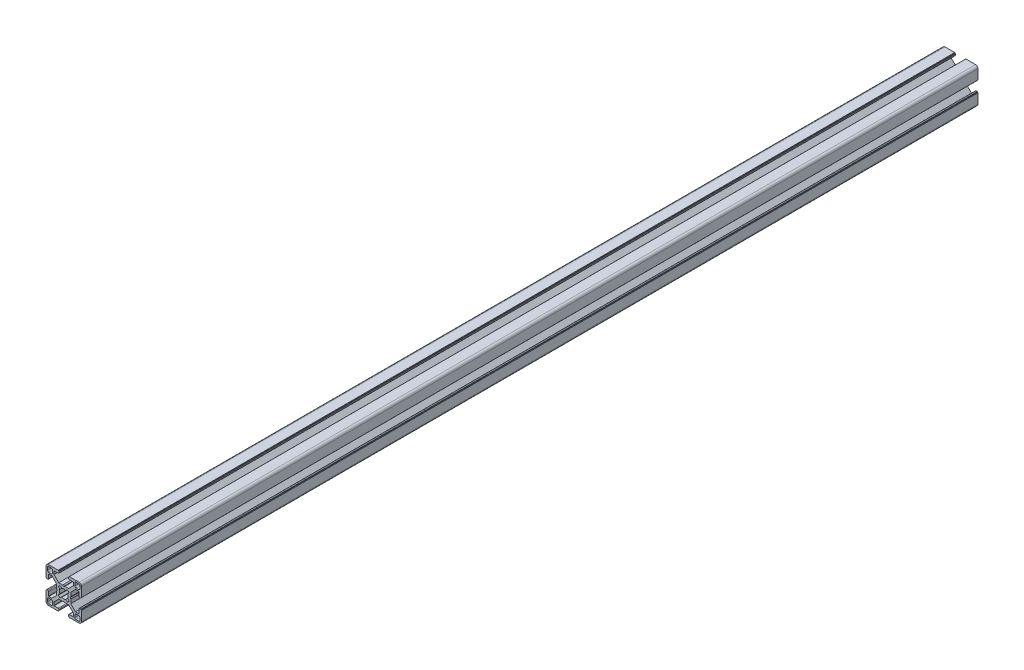
SolidWorks part; units mm, degrees
material "6063-T5"
ref_plane "前视基准面" through (0, 0, 0) normal (0, 0, 1) x (1, 0, 0)
ref_plane "上视基准面" through (0, 0, 0) normal (0, 1, 0) x (1, 0, 0)
ref_plane "右视基准面" through (0, 0, 0) normal (1, 0, 0) x (0, 0, -1)
ref_plane "基准面4" through (0, 0, 25) normal (0, 0, 1) x (1, 0, 0)
sketch "草图1" plane through (0, 0, 25) normal (0, 0, 1) x (1, 0, 0)
  line L0 (-12.7, 13.7) -> (-10.5, 13.7)
  line L1 (-9.5, 12.7) -> (-9.5, 10.5)
  line L2 (-10.5, 9.5) -> (-12.7, 9.5)
  line L3 (-13.7, 10.5) -> (-13.7, 12.7)
  line L4 (-10.5, -13.7) -> (-12.7, -13.7)
  line L5 (-13.7, -12.7) -> (-13.7, -10.5)
  line L6 (-12.7, -9.5) -> (-10.5, -9.5)
  line L7 (-9.5, -10.5) -> (-9.5, -12.7)
  line L8 (10.5, 13.7) -> (12.7, 13.7)
  line L9 (13.7, 12.7) -> (13.7, 10.5)
  line L10 (12.7, 9.5) -> (10.5, 9.5)
  line L11 (9.5, 10.5) -> (9.5, 12.7)
  line L12 (13.7, -10.5) -> (13.7, -12.7)
  line L13 (12.7, -13.7) -> (10.5, -13.7)
  line L14 (9.5, -12.7) -> (9.5, -10.5)
  line L15 (10.5, -9.5) -> (12.7, -9.5)
  line L16 (-3.1359, 4.5184) -> (-1.6001, 3.2806)
  line L17 (1.6001, 3.2806) -> (3.1359, 4.5184)
  line L18 (4.5053, 3.1547) -> (3.2806, 1.6001)
  line L19 (3.2806, -1.6001) -> (4.5053, -3.1547)
  line L20 (3.1359, -4.5184) -> (1.6001, -3.2806)
  line L21 (-1.6001, -3.2806) -> (-3.1359, -4.5184)
  line L22 (-4.5053, -3.1547) -> (-3.2806, -1.6001)
  line L23 (-3.2806, 1.6001) -> (-4.5053, 3.1547)
  line L24 (-4.05, 13.4) -> (-4.05, 14.3)
  line L25 (-4.25, 14.5) -> (-4.35, 14.5)
  line L26 (-4.55, 14.7) -> (-4.55, 14.8)
  line L27 (-4.75, 15) -> (-13, 15)
  line L28 (-15, 13) -> (-15, 4.75)
  line L29 (-14.8, 4.55) -> (-14.7, 4.55)
  line L30 (-14.5, 4.35) -> (-14.5, 4.25)
  line L31 (-14.3, 4.05) -> (-13.4, 4.05)
  line L32 (-12.8, 4.65) -> (-12.8, 8.05)
  line L33 (-12.6, 8.25) -> (-10.05, 8.25)
  line L34 (-10.05, 8.25) -> (-6.0045, 4.2045)
  line L35 (-6.0045, 4.2045) -> (-6.0045, 0.9)
  line L36 (-6.0045, 0.9) -> (-5.4849, 0)
  line L37 (-5.4849, 0) -> (-6.0045, -0.9)
  line L38 (-6.0045, -0.9) -> (-6.0045, -4.2045)
  line L39 (-6.0045, -4.2045) -> (-10.05, -8.25)
  line L40 (-10.05, -8.25) -> (-12.6, -8.25)
  line L41 (-12.8, -8.05) -> (-12.8, -4.65)
  line L42 (-13.4, -4.05) -> (-14.3, -4.05)
  line L43 (-14.5, -4.25) -> (-14.5, -4.35)
  line L44 (-14.7, -4.55) -> (-14.8, -4.55)
  line L45 (-15, -4.75) -> (-15, -13)
  line L46 (-13, -15) -> (-4.75, -15)
  line L47 (-4.55, -14.8) -> (-4.55, -14.7)
  line L48 (-4.35, -14.5) -> (-4.25, -14.5)
  line L49 (-4.05, -14.3) -> (-4.05, -13.4)
  line L50 (-4.65, -12.8) -> (-8.05, -12.8)
  line L51 (-8.25, -12.6) -> (-8.25, -10.05)
  line L52 (-8.25, -10.05) -> (-4.2045, -6)
  line L53 (-4.2045, -6) -> (-0.9, -6)
  line L54 (-0.9, -6) -> (0, -5.4849)
  line L55 (0, -5.4849) -> (0.9, -6)
  line L56 (0.9, -6) -> (4.2045, -6)
  line L57 (4.2045, -6) -> (8.25, -10.05)
  line L58 (8.25, -10.05) -> (8.25, -12.6)
  line L59 (8.05, -12.8) -> (4.65, -12.8)
  line L60 (4.05, -13.4) -> (4.05, -14.3)
  line L61 (4.25, -14.5) -> (4.35, -14.5)
  line L62 (4.55, -14.7) -> (4.55, -14.8)
  line L63 (4.75, -15) -> (13, -15)
  line L64 (15, -13) -> (15, -4.75)
  line L65 (14.8, -4.55) -> (14.7, -4.55)
  line L66 (14.5, -4.35) -> (14.5, -4.25)
  line L67 (14.3, -4.05) -> (13.4, -4.05)
  line L68 (12.8, -4.65) -> (12.8, -8.05)
  line L69 (12.6, -8.25) -> (10.05, -8.25)
  line L70 (10.05, -8.25) -> (6.0045, -4.2045)
  line L71 (6.0045, -4.2045) -> (6.0045, -0.9)
  line L72 (6.0045, -0.9) -> (5.4849, 0)
  line L73 (5.4849, 0) -> (6.0045, 0.9)
  line L74 (6.0045, 0.9) -> (6.0045, 4.2045)
  line L75 (6.0045, 4.2045) -> (10.05, 8.25)
  line L76 (10.05, 8.25) -> (12.6, 8.25)
  line L77 (12.8, 8.05) -> (12.8, 4.65)
  line L78 (13.4, 4.05) -> (14.3, 4.05)
  line L79 (14.5, 4.25) -> (14.5, 4.35)
  line L80 (14.7, 4.55) -> (14.8, 4.55)
  line L81 (15, 4.75) -> (15, 13)
  line L82 (13, 15) -> (4.75, 15)
  line L83 (4.55, 14.8) -> (4.55, 14.7)
  line L84 (4.35, 14.5) -> (4.25, 14.5)
  line L85 (4.05, 14.3) -> (4.05, 13.4)
  line L86 (4.65, 12.8) -> (8.05, 12.8)
  line L87 (8.25, 12.6) -> (8.25, 10.05)
  line L88 (8.25, 10.05) -> (4.2045, 6)
  line L89 (4.2045, 6) -> (0.9, 6)
  line L90 (0.9, 6) -> (0, 5.4849)
  line L91 (0, 5.4849) -> (-0.9, 6)
  line L92 (-0.9, 6) -> (-4.2045, 6)
  line L93 (-4.2045, 6) -> (-8.25, 10.05)
  line L94 (-8.25, 10.05) -> (-8.25, 12.6)
  line L95 (-8.05, 12.8) -> (-4.65, 12.8)
  arc A0 (-13.7, 12.7) -> (-12.7, 13.7) centre (-12.7, 12.7) cw
  arc A1 (-10.5, 13.7) -> (-9.5, 12.7) centre (-10.5, 12.7) cw
  arc A2 (-9.5, 10.5) -> (-10.5, 9.5) centre (-10.5, 10.5) cw
  arc A3 (-12.7, 9.5) -> (-13.7, 10.5) centre (-12.7, 10.5) cw
  arc A4 (-9.5, -12.7) -> (-10.5, -13.7) centre (-10.5, -12.7) cw
  arc A5 (-12.7, -13.7) -> (-13.7, -12.7) centre (-12.7, -12.7) cw
  arc A6 (-13.7, -10.5) -> (-12.7, -9.5) centre (-12.7, -10.5) cw
  arc A7 (-10.5, -9.5) -> (-9.5, -10.5) centre (-10.5, -10.5) cw
  arc A8 (9.5, 12.7) -> (10.5, 13.7) centre (10.5, 12.7) cw
  arc A9 (12.7, 13.7) -> (13.7, 12.7) centre (12.7, 12.7) cw
  arc A10 (13.7, 10.5) -> (12.7, 9.5) centre (12.7, 10.5) cw
  arc A11 (10.5, 9.5) -> (9.5, 10.5) centre (10.5, 10.5) cw
  arc A12 (13.7, -12.7) -> (12.7, -13.7) centre (12.7, -12.7) cw
  arc A13 (10.5, -13.7) -> (9.5, -12.7) centre (10.5, -12.7) cw
  arc A14 (9.5, -10.5) -> (10.5, -9.5) centre (10.5, -10.5) cw
  arc A15 (12.7, -9.5) -> (13.7, -10.5) centre (12.7, -10.5) cw
  arc A16 (-4.5053, 3.1547) -> (-3.1359, 4.5184) centre (0, 0) cw
  arc A17 (-1.6001, 3.2806) -> (1.6001, 3.2806) centre (0, 0) cw
  arc A18 (3.1359, 4.5184) -> (4.5053, 3.1547) centre (0, 0) cw
  arc A19 (3.2806, 1.6001) -> (3.2806, -1.6001) centre (0, 0) cw
  arc A20 (4.5053, -3.1547) -> (3.1359, -4.5184) centre (0, 0) cw
  arc A21 (1.6001, -3.2806) -> (-1.6001, -3.2806) centre (0, 0) cw
  arc A22 (-3.1359, -4.5184) -> (-4.5053, -3.1547) centre (0, 0) cw
  arc A23 (-3.2806, -1.6001) -> (-3.2806, 1.6001) centre (0, 0) cw
  arc A24 (-4.65, 12.8) -> (-4.05, 13.4) centre (-4.65, 13.4) ccw
  arc A25 (-4.05, 14.3) -> (-4.25, 14.5) centre (-4.25, 14.3) ccw
  arc A26 (-4.35, 14.5) -> (-4.55, 14.7) centre (-4.35, 14.7) cw
  arc A27 (-4.55, 14.8) -> (-4.75, 15) centre (-4.75, 14.8) ccw
  arc A28 (-13, 15) -> (-15, 13) centre (-13, 13) ccw
  arc A29 (-15, 4.75) -> (-14.8, 4.55) centre (-14.8, 4.75) ccw
  arc A30 (-14.7, 4.55) -> (-14.5, 4.35) centre (-14.7, 4.35) cw
  arc A31 (-14.5, 4.25) -> (-14.3, 4.05) centre (-14.3, 4.25) ccw
  arc A32 (-13.4, 4.05) -> (-12.8, 4.65) centre (-13.4, 4.65) ccw
  arc A33 (-12.8, 8.05) -> (-12.6, 8.25) centre (-12.6, 8.05) cw
  arc A34 (-12.6, -8.25) -> (-12.8, -8.05) centre (-12.6, -8.05) cw
  arc A35 (-12.8, -4.65) -> (-13.4, -4.05) centre (-13.4, -4.65) ccw
  arc A36 (-14.3, -4.05) -> (-14.5, -4.25) centre (-14.3, -4.25) ccw
  arc A37 (-14.5, -4.35) -> (-14.7, -4.55) centre (-14.7, -4.35) cw
  arc A38 (-14.8, -4.55) -> (-15, -4.75) centre (-14.8, -4.75) ccw
  arc A39 (-15, -13) -> (-13, -15) centre (-13, -13) ccw
  arc A40 (-4.75, -15) -> (-4.55, -14.8) centre (-4.75, -14.8) ccw
  arc A41 (-4.55, -14.7) -> (-4.35, -14.5) centre (-4.35, -14.7) cw
  arc A42 (-4.25, -14.5) -> (-4.05, -14.3) centre (-4.25, -14.3) ccw
  arc A43 (-4.05, -13.4) -> (-4.65, -12.8) centre (-4.65, -13.4) ccw
  arc A44 (-8.05, -12.8) -> (-8.25, -12.6) centre (-8.05, -12.6) cw
  arc A45 (8.25, -12.6) -> (8.05, -12.8) centre (8.05, -12.6) cw
  arc A46 (4.65, -12.8) -> (4.05, -13.4) centre (4.65, -13.4) ccw
  arc A47 (4.05, -14.3) -> (4.25, -14.5) centre (4.25, -14.3) ccw
  arc A48 (4.35, -14.5) -> (4.55, -14.7) centre (4.35, -14.7) cw
  arc A49 (4.55, -14.8) -> (4.75, -15) centre (4.75, -14.8) ccw
  arc A50 (13, -15) -> (15, -13) centre (13, -13) ccw
  arc A51 (15, -4.75) -> (14.8, -4.55) centre (14.8, -4.75) ccw
  arc A52 (14.7, -4.55) -> (14.5, -4.35) centre (14.7, -4.35) cw
  arc A53 (14.5, -4.25) -> (14.3, -4.05) centre (14.3, -4.25) ccw
  arc A54 (13.4, -4.05) -> (12.8, -4.65) centre (13.4, -4.65) ccw
  arc A55 (12.8, -8.05) -> (12.6, -8.25) centre (12.6, -8.05) cw
  arc A56 (12.6, 8.25) -> (12.8, 8.05) centre (12.6, 8.05) cw
  arc A57 (12.8, 4.65) -> (13.4, 4.05) centre (13.4, 4.65) ccw
  arc A58 (14.3, 4.05) -> (14.5, 4.25) centre (14.3, 4.25) ccw
  arc A59 (14.5, 4.35) -> (14.7, 4.55) centre (14.7, 4.35) cw
  arc A60 (14.8, 4.55) -> (15, 4.75) centre (14.8, 4.75) ccw
  arc A61 (15, 13) -> (13, 15) centre (13, 13) ccw
  arc A62 (4.75, 15) -> (4.55, 14.8) centre (4.75, 14.8) ccw
  arc A63 (4.55, 14.7) -> (4.35, 14.5) centre (4.35, 14.7) cw
  arc A64 (4.25, 14.5) -> (4.05, 14.3) centre (4.25, 14.3) ccw
  arc A65 (4.05, 13.4) -> (4.65, 12.8) centre (4.65, 13.4) ccw
  arc A66 (8.05, 12.8) -> (8.25, 12.6) centre (8.05, 12.6) cw
  arc A67 (-8.25, 12.6) -> (-8.05, 12.8) centre (-8.05, 12.6) cw
extrude "凸台-拉伸1" add sketch "草图1" against normal blind 760
